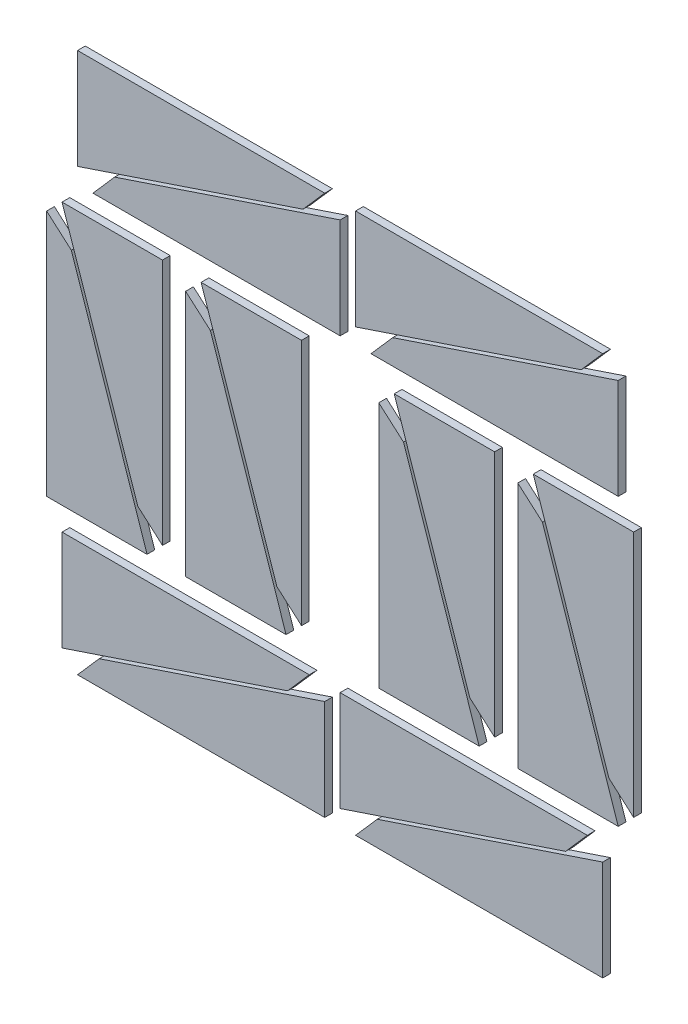
SolidWorks part; units mm, degrees
ref_plane "Front Plane" through (0, 0, 0) normal (0, 0, 1) x (1, 0, 0)
ref_plane "Top Plane" through (0, 0, 0) normal (0, 1, 0) x (1, 0, 0)
ref_plane "Right Plane" through (0, 0, 0) normal (1, 0, 0) x (0, 0, -1)
sketch "20" [suppressed] plane through (0, 0, 0) normal (0, 0, 1) x (1, 0, 0)
  line L0 (17, 0) -> (77, 0) construction
  line L1 (94, 17) -> (94, 77) construction
  line L2 (77, 94) -> (17, 94) construction
  line L3 (0, 77) -> (0, 17) construction
  line L4 (0, 17) -> (4.7574, 17) construction
  line L5 (6.8787, 16.1213) -> (16.1213, 6.8787) construction
  line L6 (17, 4.7574) -> (17, 0) construction
  line L7 (77, 0) -> (77, 4.7574) construction
  line L8 (77.8787, 6.8787) -> (87.1213, 16.1213) construction
  line L9 (89.2426, 17) -> (94, 17) construction
  line L10 (17, 94) -> (17, 89.2426) construction
  line L11 (16.1213, 87.1213) -> (6.8787, 77.8787) construction
  line L12 (4.7574, 77) -> (0, 77) construction
  line L13 (94, 77) -> (89.2426, 77) construction
  line L14 (87.1213, 77.8787) -> (77.8787, 87.1213) construction
  line L15 (77, 89.2426) -> (77, 94) construction
  arc A0 (6.8787, 16.1213) -> (4.7574, 17) centre (4.7574, 14) ccw construction
  arc A1 (17, 4.7574) -> (16.1213, 6.8787) centre (14, 4.7574) ccw construction
  arc A2 (77.8787, 6.8787) -> (77, 4.7574) centre (80, 4.7574) ccw construction
  arc A3 (89.2426, 17) -> (87.1213, 16.1213) centre (89.2426, 14) ccw construction
  arc A4 (16.1213, 87.1213) -> (17, 89.2426) centre (14, 89.2426) ccw construction
  arc A5 (4.7574, 77) -> (6.8787, 77.8787) centre (4.7574, 80) ccw construction
  arc A6 (87.1213, 77.8787) -> (89.2426, 77) centre (89.2426, 80) ccw construction
  arc A7 (77, 89.2426) -> (77.8787, 87.1213) centre (80, 89.2426) ccw construction
sketch "21" plane through (0, 0, 0) normal (0, 0, 1) x (1, 0, 0)
  line L0 (45, 12) -> (13, 12)
  line L1 (13, 12) -> (15.8, 15.2)
  line L2 (15.8, 15.2) -> (45, 25)
  line L3 (45, 25) -> (45, 12)
  line L4 (11, 27) -> (43, 27)
  line L5 (43, 27) -> (40.2, 23.8)
  line L6 (40.2, 23.8) -> (11, 14)
  line L7 (11, 14) -> (11, 27)
  line L8 (47, 27) -> (79, 27)
  line L9 (79, 27) -> (76.2, 23.8)
  line L10 (76.2, 23.8) -> (47, 14)
  line L11 (47, 14) -> (47, 27)
  line L12 (81, 12) -> (49, 12)
  line L13 (49, 12) -> (51.8, 15.2)
  line L14 (51.8, 15.2) -> (81, 25)
  line L15 (81, 25) -> (81, 12)
  line L16 (9, 30) -> (9, 62)
  line L17 (9, 62) -> (12.2, 59.2)
  line L18 (12.2, 59.2) -> (22, 30)
  line L19 (22, 30) -> (9, 30)
  line L20 (24, 64) -> (24, 32)
  line L21 (24, 32) -> (20.8, 34.8)
  line L22 (20.8, 34.8) -> (11, 64)
  line L23 (11, 64) -> (24, 64)
  line L24 (27, 30) -> (27, 62)
  line L25 (27, 62) -> (30.2, 59.2)
  line L26 (30.2, 59.2) -> (40, 30)
  line L27 (40, 30) -> (27, 30)
  line L28 (42, 64) -> (42, 32)
  line L29 (42, 32) -> (38.8, 34.8)
  line L30 (38.8, 34.8) -> (29, 64)
  line L31 (29, 64) -> (42, 64)
  line L32 (52, 30) -> (52, 62)
  line L33 (52, 62) -> (55.2, 59.2)
  line L34 (55.2, 59.2) -> (65, 30)
  line L35 (65, 30) -> (52, 30)
  line L36 (67, 64) -> (67, 32)
  line L37 (67, 32) -> (63.8, 34.8)
  line L38 (63.8, 34.8) -> (54, 64)
  line L39 (54, 64) -> (67, 64)
  line L40 (70, 30) -> (70, 62)
  line L41 (70, 62) -> (73.2, 59.2)
  line L42 (73.2, 59.2) -> (83, 30)
  line L43 (83, 30) -> (70, 30)
  line L44 (85, 64) -> (85, 32)
  line L45 (85, 32) -> (81.8, 34.8)
  line L46 (81.8, 34.8) -> (72, 64)
  line L47 (72, 64) -> (85, 64)
  line L48 (47, 67) -> (15, 67)
  line L49 (15, 67) -> (17.8, 70.2)
  line L50 (17.8, 70.2) -> (47, 80)
  line L51 (47, 80) -> (47, 67)
  line L52 (13, 82) -> (45, 82)
  line L53 (45, 82) -> (42.2, 78.8)
  line L54 (42.2, 78.8) -> (13, 69)
  line L55 (13, 69) -> (13, 82)
  line L56 (49, 82) -> (81, 82)
  line L57 (81, 82) -> (78.2, 78.8)
  line L58 (78.2, 78.8) -> (49, 69)
  line L59 (49, 69) -> (49, 82)
  line L60 (83, 67) -> (51, 67)
  line L61 (51, 67) -> (53.8, 70.2)
  line L62 (53.8, 70.2) -> (83, 80)
  line L63 (83, 80) -> (83, 67)
extrude "Boss-Extrude1" add sketch "21" along normal blind 1
